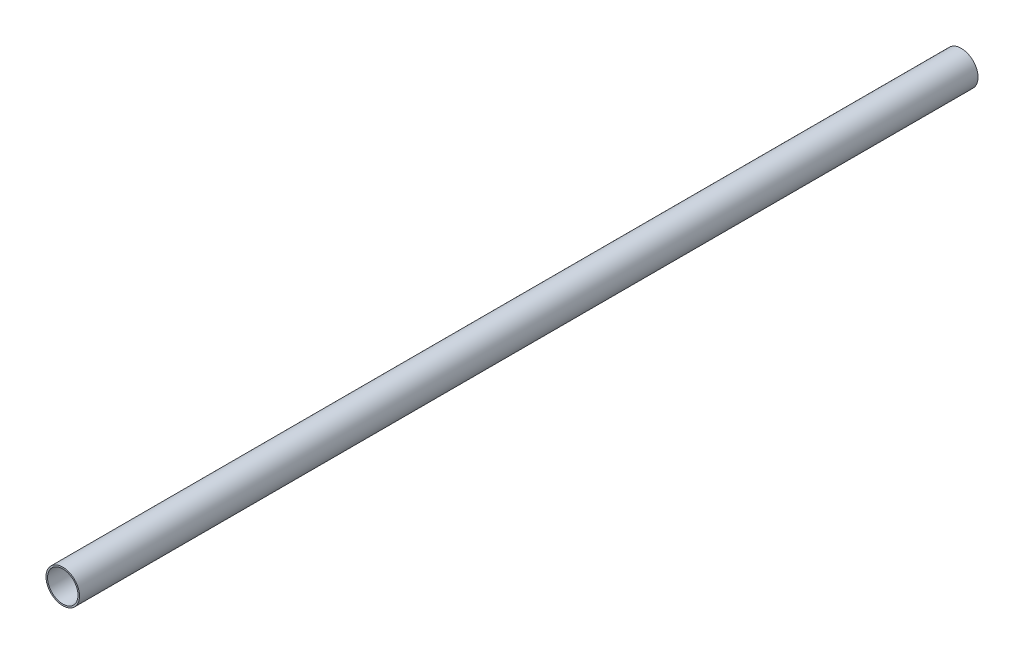
SolidWorks part; units mm, degrees
material "A-Glass Fiber"
ref_plane "Front Plane" through (0, 0, 0) normal (0, 0, 1) x (1, 0, 0)
ref_plane "Top Plane" through (0, 0, 0) normal (0, 1, 0) x (1, 0, 0)
ref_plane "Right Plane" through (0, 0, 0) normal (1, 0, 0) x (0, 0, -1)
sketch "Sketch1" plane through (0, 0, 0) normal (0, 0, 1) x (1, 0, 0)
  circle A0 centre (0, 0) radius 25.4
  circle A1 centre (0, 0) radius 27.94
  dimension "D1" = 50.8
  dimension "D2" = 55.88
extrude "Boss-Extrude1" add sketch "Sketch1" along normal blind 1498.6
